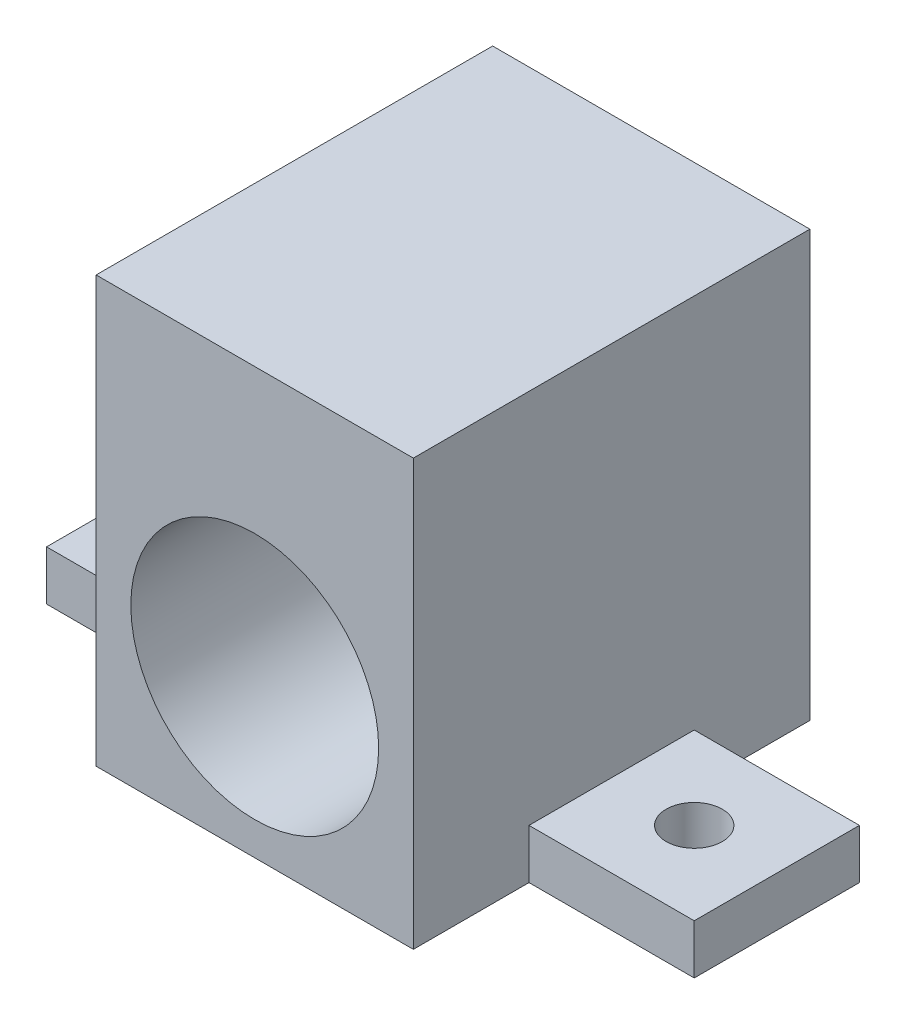
SolidWorks part; units mm, degrees
ref_plane "Front Plane" through (0, 0, 0) normal (0, 0, 1) x (1, 0, 0)
ref_plane "Top Plane" through (0, 0, 0) normal (0, 1, 0) x (1, 0, 0)
ref_plane "Right Plane" through (0, 0, 0) normal (1, 0, 0) x (0, 0, -1)
sketch "Sketch1" plane through (0, 0, 0) normal (0, 1, 0) x (1, 0, 0)
  line L0 (-9.6, 5) -> (-9.6, 12)
  line L1 (-9.6, 12) -> (9.6, 12)
  line L2 (9.6, 12) -> (9.6, 5)
  line L3 (9.6, 5) -> (19.6, 5)
  line L4 (19.6, 5) -> (19.6, -5)
  line L5 (19.6, -5) -> (9.6, -5)
  line L6 (9.6, -5) -> (9.6, -12)
  line L7 (9.6, -12) -> (-9.6, -12)
  line L8 (-9.6, -12) -> (-9.6, -5)
  line L9 (-9.6, -5) -> (-19.6, -5)
  line L10 (-19.6, -5) -> (-19.6, 5)
  line L11 (-19.6, 5) -> (-9.6, 5)
  circle A0 centre (-14.6, 0) radius 1.7
  circle A1 centre (14.6, 0) radius 1.7
  dimension "D8" = 3.4
  dimension "D1" = 7
  dimension "D2" = 17
  dimension "D3" = 10
  dimension "D4" = 29.2
  dimension "D5" = 5
  dimension "D6" = 5
  dimension "D7" = 12
  dimension "D9" = 19.6
  dimension "D10" = 12
extrude "Boss-Extrude1" add sketch "Sketch1" along normal blind 3
sketch "Sketch2" plane through (0, 3, 0) normal (0, 1, 0) x (1, 0, 0)
  line L1 (9.6, 12) -> (-9.6, 12)
  line L2 (9.6, 12) -> (9.6, -12)
  line L3 (9.6, -12) -> (-9.6, -12)
  line L4 (-9.6, 12) -> (-9.6, -12)
extrude "Boss-Extrude2" add sketch "Sketch2" along normal blind 22.752
sketch "Sketch3" plane through (0, 0, 12) normal (0, 0, 1) x (1, 0, 0)
  line L2 (-9.6, 25.752) -> (-9.6, 0) construction
  line L3 (-9.6, 0) -> (9.6, 0) construction
  circle A0 centre (0, 9.5) radius 7.5
  point P6 (0.1436, 6.0964)
  dimension "D1" = 15
  dimension "D2" = 9.6
  dimension "D3" = 9.5
extrude "Cut-Extrude1" cut sketch "Sketch3" against normal through all
